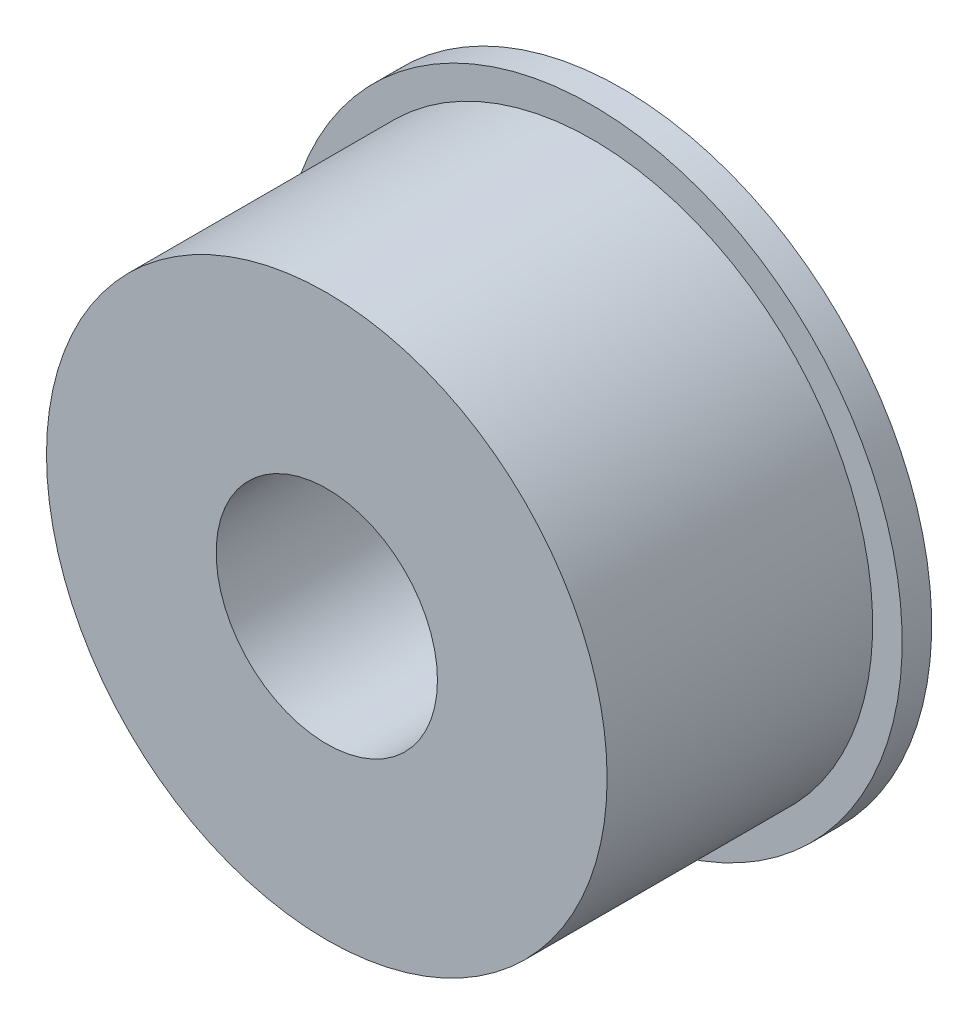
SolidWorks part; units mm, degrees
other "导向块"
ref_plane "前视基准面" through (0, 0, 0) normal (0, 0, 1) x (1, 0, 0)
ref_plane "上视基准面" through (0, 0, 0) normal (0, 1, 0) x (1, 0, 0)
ref_plane "右视基准面" through (0, 0, 0) normal (1, 0, 0) x (0, 0, -1)
other "Configuration Table"
sketch "草图1" plane through (0, 0, 0) normal (0, 0, 1) x (1, 0, 0)
  circle A0 centre (0, 0) radius 7.5
  circle A1 centre (0, 0) radius 19
  dimension "D1" = 15
  dimension "D2" = 38
extrude "凸台-拉伸1" add sketch "草图1" along normal blind 20
sketch "草图2" plane through (0, 0, 0) normal (0, 0, -1) x (-1, 0, 0)
  circle A1 centre (0, 0) radius 21
  circle A2 centre (0, 0) radius 19 construction
  circle M1 centre (0, 0) radius 19
  dimension "D1" = 2
extrude "凸台-拉伸2" add sketch "草图2" against normal blind 2 contours A1 M1
